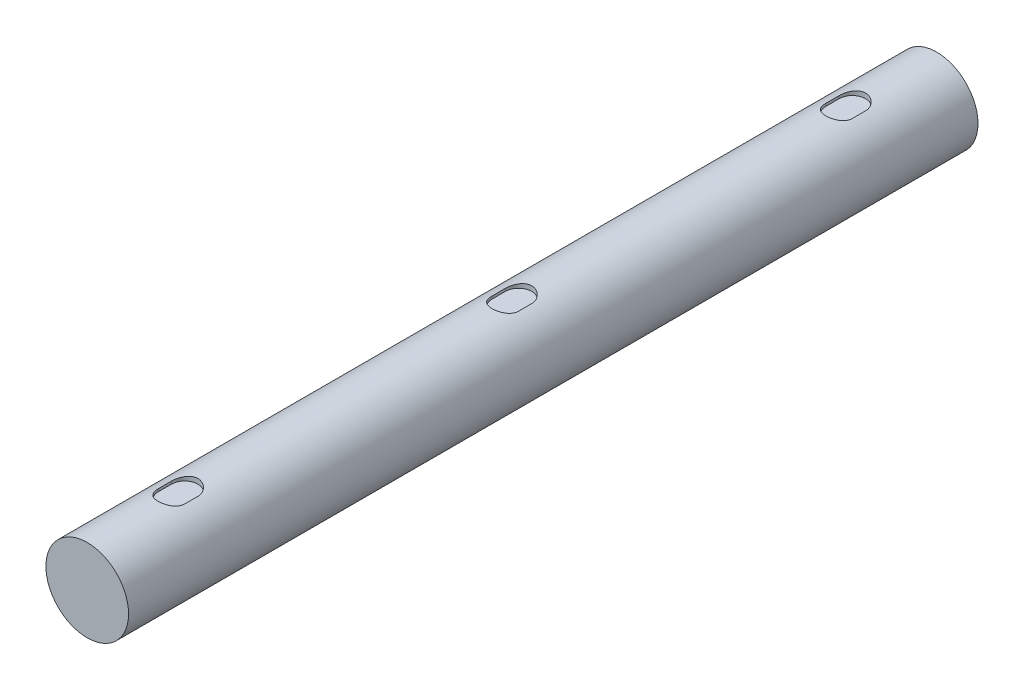
SolidWorks part; units mm, degrees
ref_plane "前视基准面" through (0, 0, 0) normal (0, 0, 1) x (1, 0, 0)
ref_plane "上视基准面" through (0, 0, 0) normal (0, 1, 0) x (1, 0, 0)
ref_plane "右视基准面" through (0, 0, 0) normal (1, 0, 0) x (0, 0, -1)
sketch "草图1" plane through (0, 0, 0) normal (0, 0, 1) x (1, 0, 0)
  circle A0 centre (0, 0) radius 12.5
extrude "凸台-拉伸1" add sketch "草图1" along normal blind 257
ref_plane "基准面4" through (0, 12, 0) normal (0, 1, 0) x (1, 0, 0)
sketch "草图6" plane through (0, 12, 0) normal (0, 1, 0) x (1, 0, 0)
  line L0 (0, 0) -> (0, -60) construction
  line L1 (0, -62) -> (0, -58) construction
  line L2 (-4, -62) -> (-4, -58)
  line L3 (-17.0621, -60) -> (26.6661, -60) construction
  line L4 (-21.3208, -27.5) -> (30.3376, -27.5) construction
  line L17 (4, -62) -> (4, -58)
  line L18 (0, -29.5) -> (0, -25.5) construction
  line L19 (-4, -29.5) -> (-4, -25.5)
  line L20 (4, -29.5) -> (4, -25.5)
  line L21 (0, -90.5) -> (0, -94.5) construction
  line L22 (-4, -90.5) -> (-4, -94.5)
  line L23 (4, -90.5) -> (4, -94.5)
  line L24 (0, 0) -> (0, -128.5) construction
  line L25 (-35.3839, -82.6225) -> (65.1755, -82.6225) construction
  line L26 (0, -126.5) -> (0, -130.5) construction
  line L27 (-4, -126.5) -> (-4, -130.5)
  line L28 (4, -126.5) -> (4, -130.5)
  arc A0 (-4, -62) -> (4, -62) centre (0, -62) ccw
  arc A1 (4, -58) -> (-4, -58) centre (0, -58) ccw
  arc A2 (-4, -29.5) -> (4, -29.5) centre (0, -29.5) ccw
  arc A3 (4, -25.5) -> (-4, -25.5) centre (0, -25.5) ccw
  arc A4 (-4, -90.5) -> (4, -90.5) centre (0, -90.5) cw
  arc A5 (4, -94.5) -> (-4, -94.5) centre (0, -94.5) cw
  arc A6 (-4, -126.5) -> (4, -126.5) centre (0, -126.5) cw
  arc A7 (4, -130.5) -> (-4, -130.5) centre (0, -130.5) cw
  point P7 (0, -60)
  point P17 (0, -27.5)
  point P23 (-4, -27.5)
  point P24 (0, -33.5)
  point P25 (0, -21.5)
  point P28 (0, -92.5)
  point P36 (0, -128.5)
  dimension "D1" = 32.5
  dimension "D2" = 8
  dimension "D3" = 12
  dimension "D4" = 12
  dimension "D5" = 8
  dimension "D6" = 82.6225
extrude "切除-拉伸1" cut sketch "草图6" against normal mid plane 1.95 contours A3 L19 A2 L20 | A6 L28 A7 L27
ref_plane "基准面5" through (0, 0, 128.5) normal (0, 0, -1) x (-1, 0, 0)
mirror "镜向1" about plane through (0, 0, 128.5) normal (0, 0, -1) of "切除-拉伸1"
